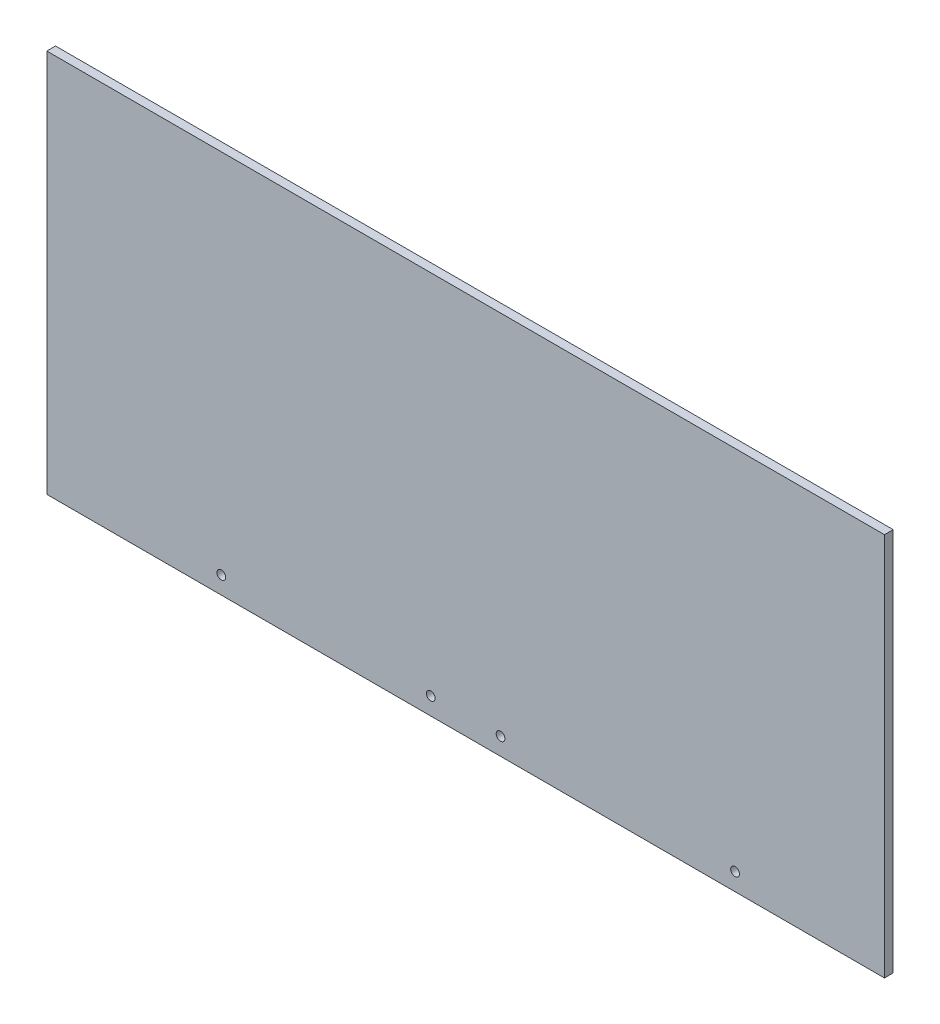
SolidWorks part; units mm, degrees
ref_plane "Front Plane" through (0, 0, 0) normal (0, 0, 1) x (1, 0, 0)
ref_plane "Top Plane" through (0, 0, 0) normal (0, 1, 0) x (1, 0, 0)
ref_plane "Right Plane" through (0, 0, 0) normal (1, 0, 0) x (0, 0, -1)
sketch "Sketch1" plane through (0, 0, 0) normal (0, 0, 1) x (1, 0, 0)
  line L0 (-324.8121, -188.8323) -> (284.7879, -188.8323) construction
  line L1 (-172.4121, 77.8677) -> (-20.0121, 77.8677)
  line L2 (-172.4121, 77.8677) -> (-172.4121, -201.5323)
  line L3 (-172.4121, -201.5323) -> (-20.0121, -201.5323)
  line L4 (-20.0121, 77.8677) -> (-20.0121, -201.5323)
  line L5 (-172.4121, 77.8677) -> (-20.0121, -201.5323) construction
  line L6 (-172.4121, -201.5323) -> (-20.0121, 77.8677) construction
  line L7 (-20.0121, 77.8677) -> (132.3879, 77.8677)
  line L8 (-20.0121, 77.8677) -> (-20.0121, -201.5323)
  line L9 (-20.0121, -201.5323) -> (132.3879, -201.5323)
  line L10 (132.3879, 77.8677) -> (132.3879, -201.5323)
  line L11 (-20.0121, 77.8677) -> (132.3879, -201.5323) construction
  line L12 (-20.0121, -201.5323) -> (132.3879, 77.8677) construction
  line L13 (132.3879, 77.8677) -> (284.7879, 77.8677)
  line L14 (132.3879, 77.8677) -> (132.3879, -201.5323)
  line L15 (132.3879, -201.5323) -> (284.7879, -201.5323)
  line L16 (284.7879, 77.8677) -> (284.7879, -201.5323)
  line L17 (132.3879, 77.8677) -> (284.7879, -201.5323) construction
  line L18 (132.3879, -201.5323) -> (284.7879, 77.8677) construction
  line L19 (-172.4121, 77.8677) -> (-324.8121, 77.8677)
  line L20 (-172.4121, 77.8677) -> (-172.4121, -201.5323)
  line L21 (-172.4121, -201.5323) -> (-324.8121, -201.5323)
  line L22 (-324.8121, 77.8677) -> (-324.8121, -201.5323)
  line L23 (-172.4121, 77.8677) -> (-324.8121, -201.5323) construction
  line L24 (-172.4121, -201.5323) -> (-324.8121, 77.8677) construction
  circle A0 centre (-197.8121, -188.8323) radius 3.175
  circle A1 centre (-45.4121, -188.8323) radius 3.175
  circle A2 centre (5.3879, -188.8323) radius 3.175
  circle A3 centre (176.0505, -188.8323) radius 3.175
  point P4 (-96.2121, -61.8323)
  point P7 (56.1879, -61.8323)
  point P10 (208.5879, -61.8323)
  point P14 (-248.6121, -61.8323)
  dimension "D8" = 6.35
  dimension "D1" = 152.4
  dimension "D2" = 12.7
  dimension "D3" = 152.4
  dimension "D4" = 50.8
  dimension "D5" = 170.6626
  dimension "D6" = 25.4
  dimension "D7" = 279.4
extrude "Boss-Extrude1" add sketch "Sketch1" along normal blind 6.35 contours L19 L22 L21 L2 A0 | L4 L1 L2 L3 A1 | L10 L7 L4 L9 A2 | L16 L13 L10 L15 A3
